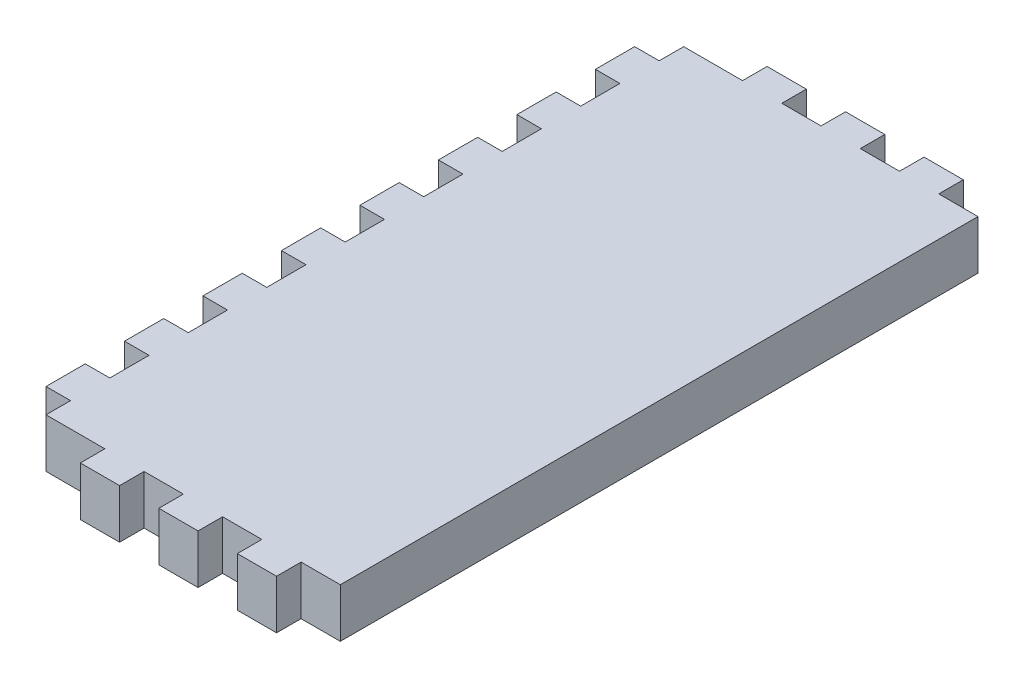
SolidWorks part; units mm, degrees
ref_plane "Front Plane" through (0, 0, 0) normal (0, 0, 1) x (1, 0, 0)
ref_plane "Top Plane" through (0, 0, 0) normal (0, 1, 0) x (1, 0, 0)
ref_plane "Right Plane" through (0, 0, 0) normal (1, 0, 0) x (0, 0, -1)
sketch "Sketch1" plane through (0, 0, 0) normal (0, 1, 0) x (1, 0, 0)
  line L1 (-19.05, -41.275) -> (19.05, -41.275)
  line L2 (-19.05, -41.275) -> (-19.05, 41.275)
  line L3 (-19.05, 41.275) -> (19.05, 41.275)
  line L4 (19.05, -41.275) -> (19.05, 41.275)
  line L5 (-19.05, -41.275) -> (19.05, 41.275) construction
  line L6 (-19.05, 41.275) -> (19.05, -41.275) construction
  line L11 (-12.7, -34.925) -> (12.7, 34.925) construction
  line L12 (-12.7, 34.925) -> (12.7, -34.925) construction
  point P0 (0, 0)
  point P5 (0, 0)
  dimension "D1" = 38.1
  dimension "D2" = 82.55
extrude "Boss-Extrude1" add sketch "Sketch1" along normal blind 6.35
sketch "Sketch2" plane through (0, 0, 0) normal (0, -1, 0) x (-1, 0, 0)
  line L0 (-19.05, 41.275) -> (19.05, 41.275) construction
  line L1 (-13.97, 41.275) -> (-8.89, 41.275)
  line L2 (-13.97, 41.275) -> (-13.97, 44.45)
  line L3 (-13.97, 44.45) -> (-8.89, 44.45)
  line L4 (-8.89, 41.275) -> (-8.89, 44.45)
  line L5 (19.05, 41.275) -> (19.05, -41.275) construction
  line L6 (19.05, 38.1) -> (22.225, 38.1)
  line L7 (19.05, 38.1) -> (19.05, 33.02)
  line L8 (19.05, 33.02) -> (22.225, 33.02)
  line L9 (22.225, 38.1) -> (22.225, 33.02)
  line L10 (-19.05, -41.275) -> (-19.05, 41.275) construction
  line L11 (-3.81, 41.275) -> (1.27, 41.275)
  line L12 (1.27, 41.275) -> (1.27, 44.45)
  line L13 (-3.81, 44.45) -> (1.27, 44.45)
  line L14 (-3.81, 41.275) -> (-3.81, 44.45)
  line L15 (6.35, 41.275) -> (11.43, 41.275)
  line L16 (11.43, 41.275) -> (11.43, 44.45)
  line L17 (6.35, 44.45) -> (11.43, 44.45)
  line L18 (6.35, 41.275) -> (6.35, 44.45)
  line L19 (19.05, 44.45) -> (22.225, 44.45) construction
  line L20 (22.225, 27.94) -> (22.225, 22.86)
  line L21 (19.05, 22.86) -> (22.225, 22.86)
  line L22 (19.05, 27.94) -> (19.05, 22.86)
  line L23 (19.05, 27.94) -> (22.225, 27.94)
  line L24 (22.225, 17.78) -> (22.225, 12.7)
  line L25 (19.05, 12.7) -> (22.225, 12.7)
  line L26 (19.05, 17.78) -> (19.05, 12.7)
  line L27 (19.05, 17.78) -> (22.225, 17.78)
  line L28 (22.225, 7.62) -> (22.225, 2.54)
  line L29 (19.05, 2.54) -> (22.225, 2.54)
  line L30 (19.05, 7.62) -> (19.05, 2.54)
  line L31 (19.05, 7.62) -> (22.225, 7.62)
  line L32 (22.225, -2.54) -> (22.225, -7.62)
  line L33 (19.05, -7.62) -> (22.225, -7.62)
  line L34 (19.05, -2.54) -> (19.05, -7.62)
  line L35 (19.05, -2.54) -> (22.225, -2.54)
  line L36 (22.225, -12.7) -> (22.225, -17.78)
  line L37 (19.05, -17.78) -> (22.225, -17.78)
  line L38 (19.05, -12.7) -> (19.05, -17.78)
  line L39 (19.05, -12.7) -> (22.225, -12.7)
  line L40 (22.225, -22.86) -> (22.225, -27.94)
  line L41 (19.05, -27.94) -> (22.225, -27.94)
  line L42 (19.05, -22.86) -> (19.05, -27.94)
  line L43 (19.05, -22.86) -> (22.225, -22.86)
  line L44 (22.225, -33.02) -> (22.225, -38.1)
  line L45 (19.05, -38.1) -> (22.225, -38.1)
  line L46 (19.05, -33.02) -> (19.05, -38.1)
  line L47 (19.05, -33.02) -> (22.225, -33.02)
  line L48 (0, 0) -> (-8.0736, 0) construction
  line L49 (6.35, -41.275) -> (6.35, -44.45)
  line L50 (6.35, -44.45) -> (11.43, -44.45)
  line L51 (11.43, -41.275) -> (11.43, -44.45)
  line L52 (6.35, -41.275) -> (11.43, -41.275)
  line L53 (-3.81, -41.275) -> (-3.81, -44.45)
  line L54 (-3.81, -44.45) -> (1.27, -44.45)
  line L55 (1.27, -41.275) -> (1.27, -44.45)
  line L56 (-3.81, -41.275) -> (1.27, -41.275)
  line L57 (-8.89, -41.275) -> (-8.89, -44.45)
  line L58 (-13.97, -44.45) -> (-8.89, -44.45)
  line L59 (-13.97, -41.275) -> (-13.97, -44.45)
  line L60 (-13.97, -41.275) -> (-8.89, -41.275)
  dimension "D1" = 5.08
  dimension "D2" = 5.08
  dimension "D3" = 3.175
  dimension "D4" = 6.35
  dimension "D5" = 5.08
  dimension "D6" = 3.175
extrude "Boss-Extrude2" add sketch "Sketch2" against normal blind 6.35
